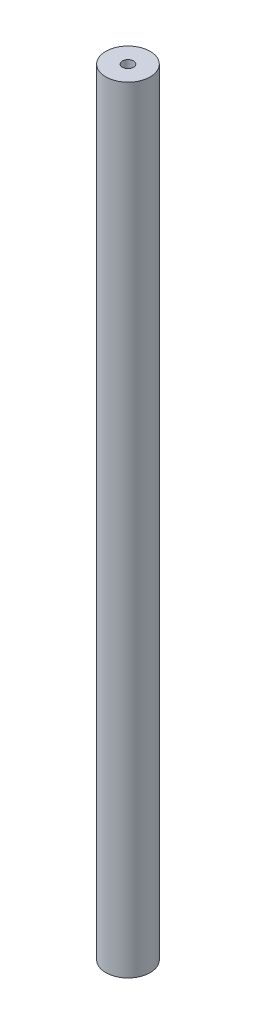
SolidWorks part; units mm, degrees
ref_plane "Front Plane" through (0, 0, 0) normal (0, 0, 1) x (1, 0, 0)
ref_plane "Top Plane" through (0, 0, 0) normal (0, 1, 0) x (1, 0, 0)
ref_plane "Right Plane" through (0, 0, 0) normal (1, 0, 0) x (0, 0, -1)
sketch "Sketch1" plane through (0, 0, 0) normal (0, 1, 0) x (1, 0, 0)
  circle A0 centre (0, 0) radius 12.7
  dimension "D1" = 25.4
extrude "Boss-Extrude1" add sketch "Sketch1" along normal blind 444.5
sketch "Sketch2" plane through (0, 444.5, 0) normal (0, 1, 0) x (1, 0, 0)
  circle A0 centre (0, 0) radius 3.175
  dimension "D1" = 6.35
extrude "Cut-Extrude1" cut sketch "Sketch2" against normal blind 25.4
ref_plane "Plane1" through (0, 222.25, 0) normal (0, 1, 0) x (1, 0, 0)
mirror "Mirror1" about plane through (0, 222.25, 0) normal (0, 1, 0) of "Cut-Extrude1"
